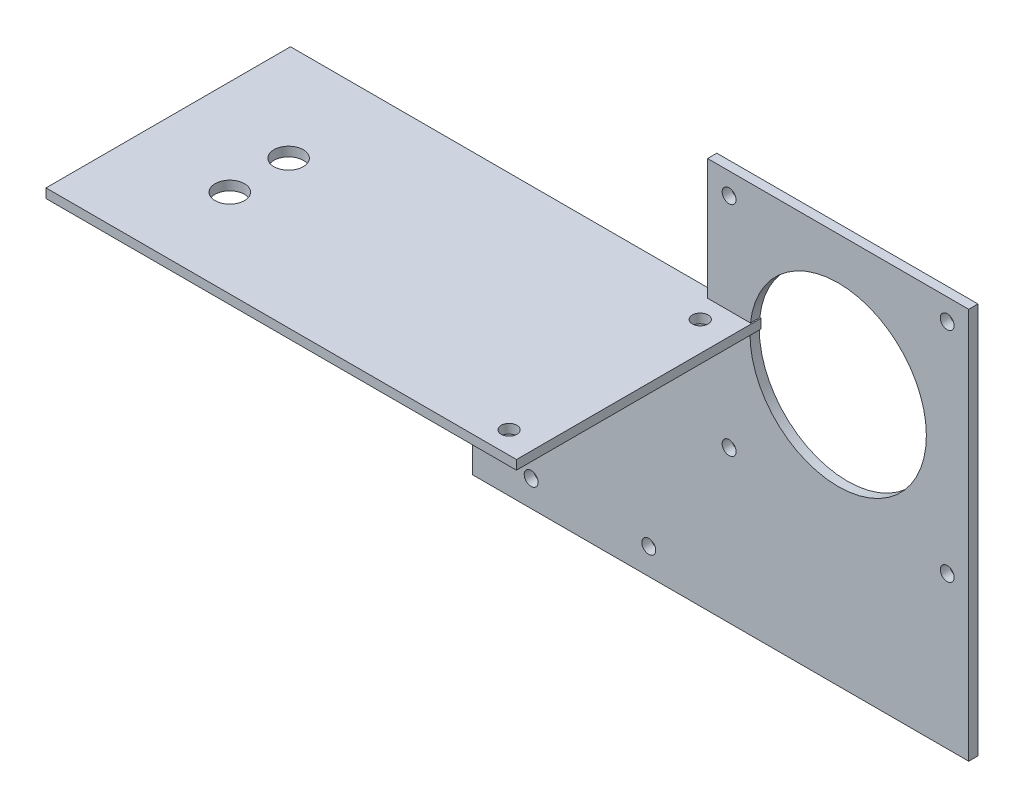
SolidWorks part; units mm, degrees
material "Galvanized Steel"
ref_plane "Front Plane" through (0, 0, 0) normal (0, 0, 1) x (1, 0, 0)
ref_plane "Top Plane" through (0, 0, 0) normal (0, 1, 0) x (1, 0, 0)
ref_plane "Right Plane" through (0, 0, 0) normal (1, 0, 0) x (0, 0, -1)
sketch "Sketch1" plane through (0, 0, 0) normal (0, 0, 1) x (1, 0, 0)
  line L0 (12.7, 52.75) -> (38.1, 52.75) construction
  line L1 (12.7, 5.65) -> (38.1, 5.65) construction
  line L2 (0, 58.4) -> (0, 0)
  line L3 (0, 0) -> (107.2, 0)
  line L4 (55.45, 79.882) -> (102.55, 79.882) construction
  line L5 (102.55, 79.882) -> (102.55, 32.782) construction
  line L6 (12.7, 52.75) -> (12.7, 5.65) construction
  line L7 (55.45, 32.782) -> (55.45, 79.882) construction
  line L8 (55.45, 32.782) -> (102.55, 32.782) construction
  line L9 (38.1, 52.75) -> (38.1, 5.65) construction
  line L10 (55.45, 79.882) -> (102.55, 32.782) construction
  line L11 (102.55, 79.882) -> (55.45, 32.782) construction
  line L12 (0, 58.4) -> (50.8, 58.4)
  line L13 (50.8, 58.4) -> (50.8, 84.532)
  line L14 (50.8, 84.532) -> (107.2, 84.532)
  line L15 (107.2, 84.532) -> (107.2, 0)
  circle A0 centre (102.55, 79.882) radius 1.5
  circle A1 centre (102.55, 32.782) radius 1.5
  circle A2 centre (55.45, 32.782) radius 1.5
  circle A3 centre (55.45, 79.882) radius 1.5
  circle A4 centre (12.7, 52.75) radius 1.5
  circle A5 centre (38.1, 52.75) radius 1.5
  circle A6 centre (12.7, 5.65) radius 1.5
  circle A7 centre (38.1, 5.65) radius 1.5
  circle A8 centre (79, 56.332) radius 19.05
  point P3 (12.7, 29.2)
  point P21 (0, 29.2)
  dimension "D3" = 3
  dimension "D10" = 38.1
  dimension "D1" = 58.4
  dimension "D2" = 107.2
  dimension "D4" = 47.1
  dimension "D5" = 47.1
  dimension "D6" = 2.068
  dimension "D7" = 25.4
  dimension "D8" = 47.1
  dimension "D9" = 12.7
  dimension "D11" = 4.65
  dimension "D12" = 4.65
  dimension "D13" = 4.65
extrude "Boss-Extrude1" add sketch "Sketch1" against normal blind 2
sketch "Sketch2" plane through (0, 0, -2) normal (0, 0, -1) x (-1, 0, 0)
  line L0 (0, 58.4) -> (41.275, 58.4)
  line L1 (0, 58.4) -> (0, 0) construction
  line L2 (0, 56.4) -> (-60.325, 56.4)
  line L3 (-60.325, 56.4) -> (-60.325, 58.4)
  line L5 (-60.325, 58.4) -> (0, 58.4)
  line L6 (41.275, 58.4) -> (41.275, 56.4)
  line L7 (41.275, 56.4) -> (0, 56.4)
  dimension "D1" = 60.325
  dimension "D2" = 2
  dimension "D3" = 41.275
extrude "Boss-Extrude2" add sketch "Sketch2" against normal blind 52.8
sketch "Sketch3" plane through (0, 58.4, 0) normal (0, 1, 0) x (1, 0, 0)
  line L0 (53.975, -4.7625) -> (53.975, -46.0375) construction
  line L2 (60.325, -50.8) -> (60.325, 2) construction
  line L3 (-41.275, -50.8) -> (60.325, -50.8) construction
  circle A0 centre (53.975, -4.7625) radius 1.7
  circle A1 centre (53.975, -46.0375) radius 1.7
  dimension "D1" = 3.4
  dimension "D2" = 41.275
  dimension "D3" = 4.7625
  dimension "D4" = 6.35
extrude "Cut-Extrude1" cut sketch "Sketch3" against normal through all
sketch "Sketch4" plane through (0, 58.4, 0) normal (0, 1, 0) x (1, 0, 0)
  line L0 (-20.6375, 2) -> (-20.6375, -50.8) construction
  line L2 (-41.275, -50.8) -> (60.325, -50.8) construction
  line L3 (-41.275, -50.8) -> (-41.275, 2) construction
  line L4 (50.8, 2) -> (-41.275, 2) construction
  circle A0 centre (-20.6375, -19.05) radius 3.175
  circle A1 centre (-20.6375, -31.75) radius 3.175
  dimension "D2" = 6.35
  dimension "D3" = 6.35
  dimension "D1" = 20.6375
  dimension "D4" = 12.7
  dimension "D5" = 19.05
extrude "Cut-Extrude2" cut sketch "Sketch4" against normal blind 10
